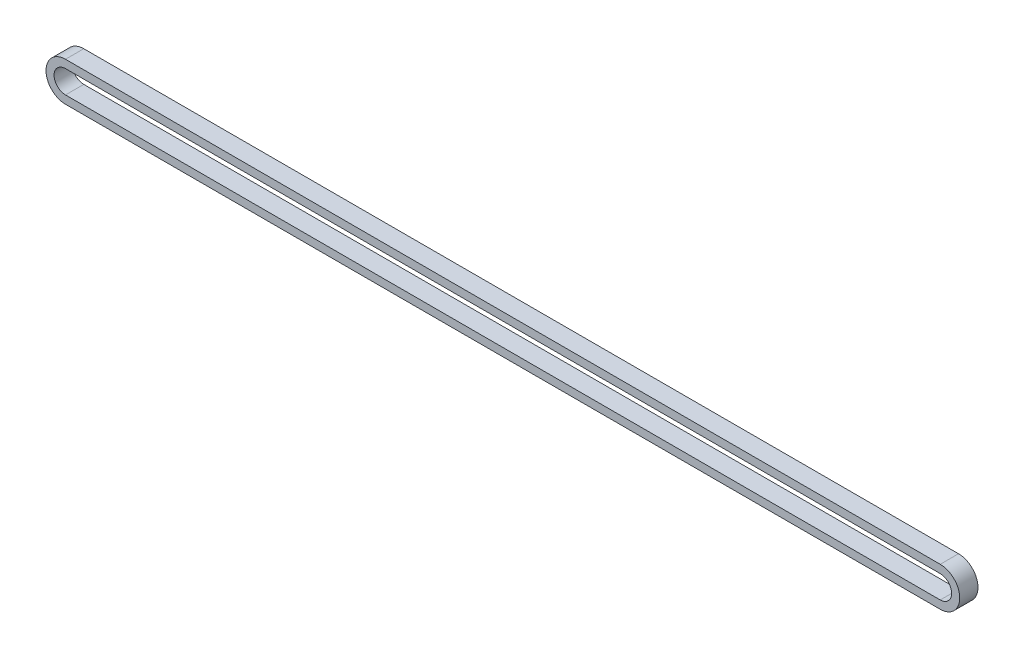
SolidWorks part; units mm, degrees
ref_plane "Front Plane" through (0, 0, 0) normal (0, 0, 1) x (1, 0, 0)
ref_plane "Top Plane" through (0, 0, 0) normal (0, 1, 0) x (1, 0, 0)
ref_plane "Right Plane" through (0, 0, 0) normal (1, 0, 0) x (0, 0, -1)
sketch "Sketch2" plane through (0, 0, 0) normal (0, 0, 1) x (1, 0, 0)
  line L0 (0, 0) -> (143.6, 0) construction
  line L1 (0, 3.2) -> (143.6, 3.2)
  line L2 (0, -3.2) -> (143.6, -3.2)
  line L3 (0, 0) -> (143.6, 0) construction
  line L4 (0, 1.872) -> (143.6, 1.872)
  line L5 (0, -1.872) -> (143.6, -1.872)
  arc A0 (0, 3.2) -> (0, -3.2) centre (0, 0) ccw
  arc A1 (143.6, -3.2) -> (143.6, 3.2) centre (143.6, 0) ccw
  arc A2 (0, 1.872) -> (0, -1.872) centre (0, 0) ccw
  arc A3 (143.6, -1.872) -> (143.6, 1.872) centre (143.6, 0) ccw
  circle A4 centre (0, 0) radius 3.2 construction
  circle A5 centre (0, 0) radius 1.872 construction
  circle A6 centre (143.6, 0) radius 3.2 construction
  circle A7 centre (143.6, 0) radius 1.872 construction
  point P4 (71.8, 0)
  point P9 (71.8, 0)
extrude "Boss-Extrude1" add sketch "Sketch2" against normal blind 3 contours L1 A1 L2 A0
